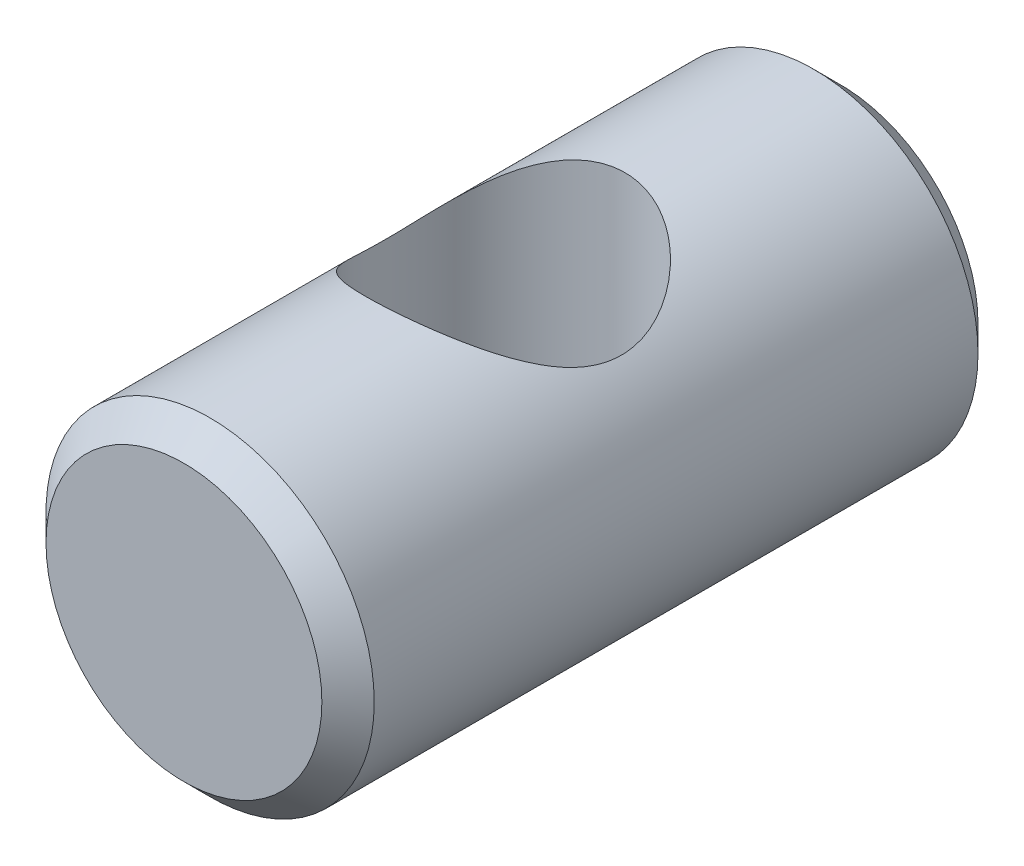
SolidWorks part; units mm, degrees
ref_plane "Front Plane" through (0, 0, 0) normal (0, 0, 1) x (1, 0, 0)
ref_plane "Top Plane" through (0, 0, 0) normal (0, 1, 0) x (1, 0, 0)
ref_plane "Right Plane" through (0, 0, 0) normal (1, 0, 0) x (0, 0, -1)
sketch "Sketch1" plane through (0, 0, 0) normal (0, 0, 1) x (1, 0, 0)
  circle A0 centre (0, 0) radius 4.765
extrude "Boss-Extrude1" add sketch "Sketch1" along normal mid plane 19.05
chamfer "Chamfer1" distance 0.76 angle 45 2 edges at (4.765, 0, -9.525) (4.765, 0, 9.525)
sketch "Sketch2" plane through (0, 0, 0) normal (0, 1, 0) x (1, 0, 0)
  circle A0 centre (-0.25, 0) radius 3.43
  dimension "D1" = 6.86
  dimension "D2" = 0.25
extrude "Cut-Extrude1" cut sketch "Sketch2" against normal through all both and the other way through all
